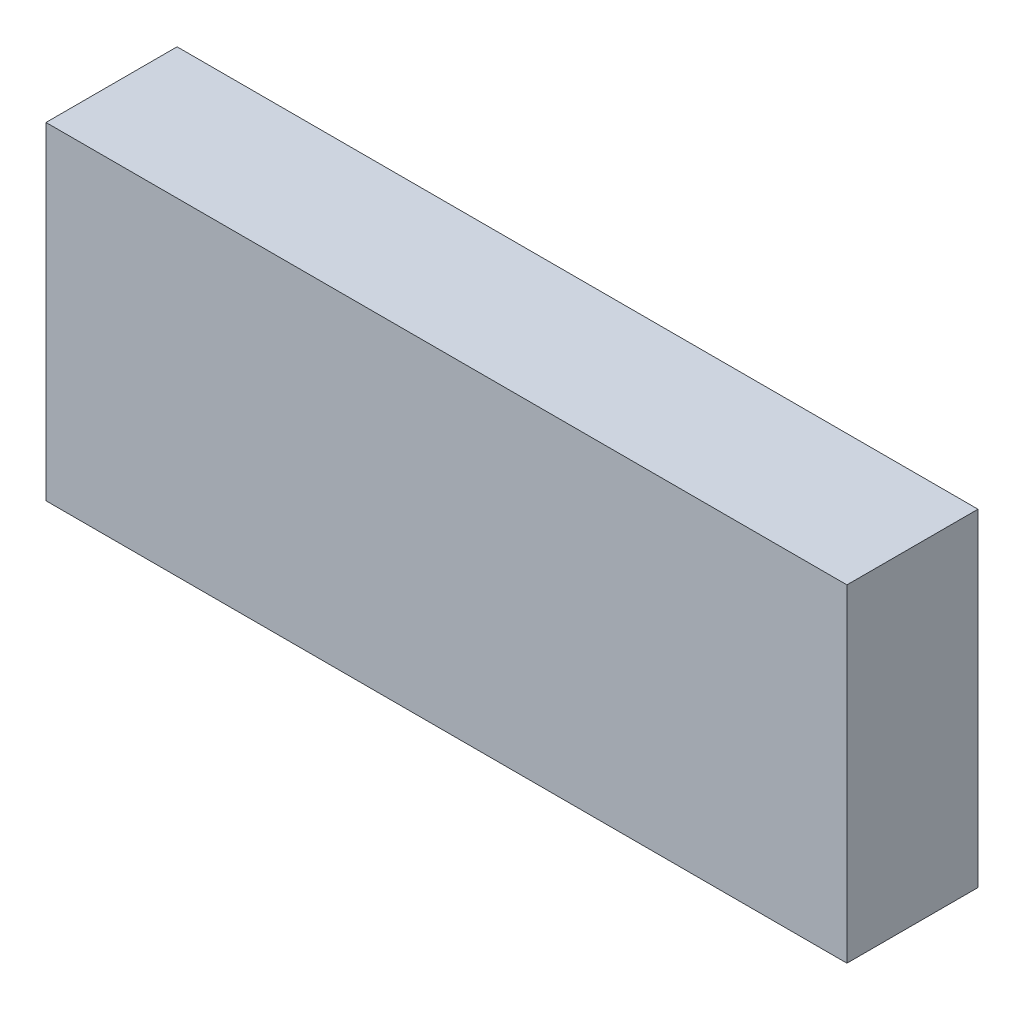
SolidWorks part; units mm, degrees
ref_plane "Front Plane" through (0, 0, 0) normal (0, 0, 1) x (1, 0, 0)
ref_plane "Top Plane" through (0, 0, 0) normal (0, 1, 0) x (1, 0, 0)
ref_plane "Right Plane" through (0, 0, 0) normal (1, 0, 0) x (0, 0, -1)
sketch "Sketch1" plane through (0, 0, 0) normal (0, 0, 1) x (1, 0, 0)
  line L1 (-47.4636, 15.3353) -> (62.5364, 15.3353)
  line L2 (-47.4636, 15.3353) -> (-47.4636, -29.6647)
  line L3 (-47.4636, -29.6647) -> (62.5364, -29.6647)
  line L4 (62.5364, 15.3353) -> (62.5364, -29.6647)
  dimension "D1" = 110
  dimension "D2" = 45
extrude "Boss-Extrude1" add sketch "Sketch1" along normal blind 18
